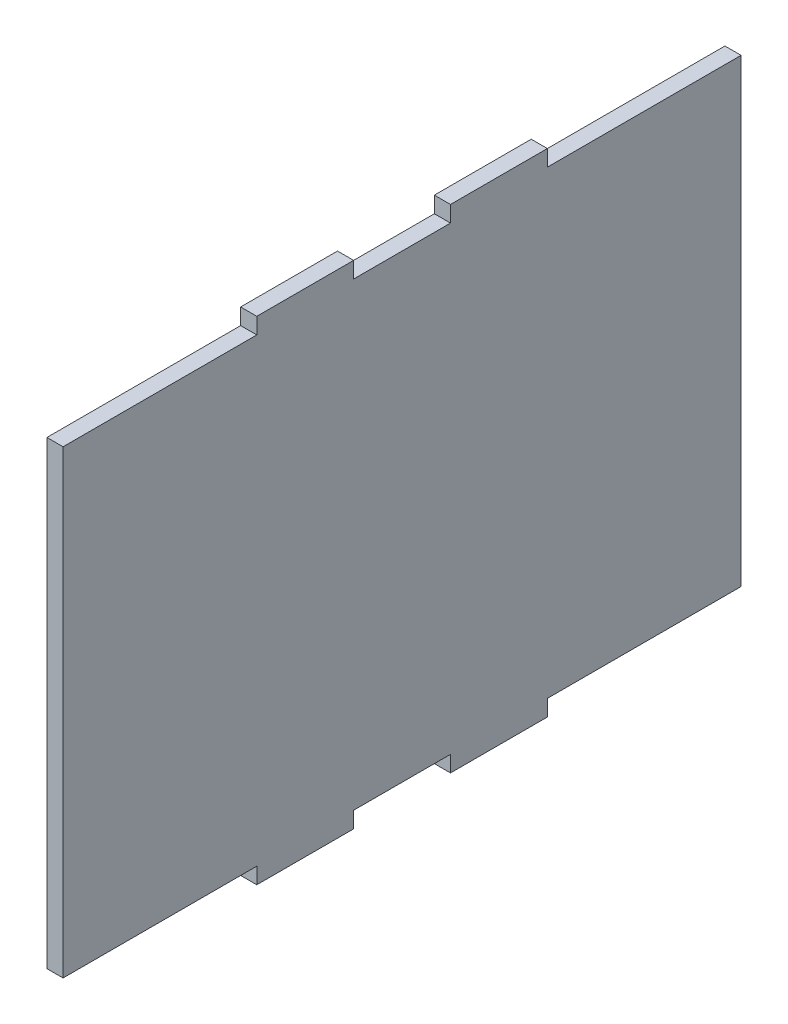
SolidWorks part; units mm, degrees
material "Acrylic (Medium-high impact)"
ref_plane "Front Plane" through (0, 0, 0) normal (0, 0, 1) x (1, 0, 0)
ref_plane "Top Plane" through (0, 0, 0) normal (0, 1, 0) x (1, 0, 0)
ref_plane "Right Plane" through (0, 0, 0) normal (1, 0, 0) x (0, 0, -1)
sketch "Sketch1" plane through (0, 0, 0) normal (1, 0, 0) x (0, 0, -1)
  line L0 (-328.8947, 211.2215) -> (-208.8947, 211.2215)
  line L1 (-208.8947, 211.2215) -> (-208.8947, 221.2215)
  line L2 (-208.8947, 221.2215) -> (-148.8947, 221.2215)
  line L3 (-148.8947, 221.2215) -> (-148.8947, 211.2215)
  line L4 (-148.8947, 211.2215) -> (-88.8947, 211.2215)
  line L5 (-88.8947, 211.2215) -> (-88.8947, 221.2215)
  line L6 (-88.8947, 221.2215) -> (-28.8947, 221.2215)
  line L7 (-28.8947, 221.2215) -> (-28.8947, 211.2215)
  line L8 (-28.8947, 211.2215) -> (91.1053, 211.2215)
  line L9 (-328.8947, 211.2215) -> (-328.8947, -73.7785)
  line L10 (91.1053, 211.2215) -> (91.1053, -73.7785)
  line L11 (-328.8947, -73.7785) -> (-208.8947, -73.7785)
  line L12 (-208.8947, -73.7785) -> (-208.8947, -83.7785)
  line L13 (-208.8947, -83.7785) -> (-148.8947, -83.7785)
  line L14 (-148.8947, -83.7785) -> (-148.8947, -73.7785)
  line L15 (-148.8947, -73.7785) -> (-88.8947, -73.7785)
  line L16 (-88.8947, -73.7785) -> (-88.8947, -83.7785)
  line L17 (-88.8947, -83.7785) -> (-28.8947, -83.7785)
  line L18 (-28.8947, -83.7785) -> (-28.8947, -73.7785)
  line L19 (-28.8947, -73.7785) -> (91.1053, -73.7785)
extrude "Boss-Extrude1" add sketch "Sketch1" along normal blind 10
